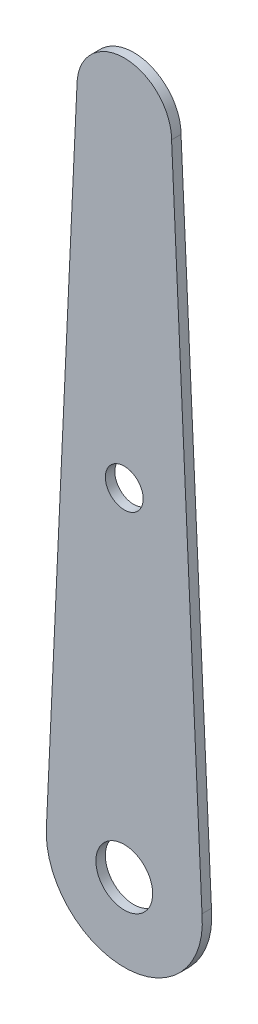
SolidWorks part; units mm, degrees
material "Galvanized Steel"
ref_plane "Front Plane" through (0, 0, 0) normal (0, 0, 1) x (1, 0, 0)
ref_plane "Top Plane" through (0, 0, 0) normal (0, 1, 0) x (1, 0, 0)
ref_plane "Right Plane" through (0, 0, 0) normal (1, 0, 0) x (0, 0, -1)
sketch "Sketch1" plane through (0, 0, 0) normal (0, 0, 1) x (1, 0, 0)
  line L0 (-16.429, -29.4883) -> (-10, 108.9829)
  line L1 (10, 108.9829) -> (16.429, -29.4883)
  arc A0 (-16.429, -29.4883) -> (16.429, -29.4883) centre (0, -31.0171) ccw
  arc A1 (10, 108.9829) -> (-10, 108.9829) centre (0, 108.9829) ccw
  circle A2 centre (0, 40.2429) radius 4
  dimension "D1" = 33
  dimension "D2" = 20
  dimension "D3" = 140
  dimension "D4" = 71.26
  dimension "D5" = 8
extrude "Boss-Extrude1" add sketch "Sketch1" along normal blind 2
sketch "Sketch2" plane through (0, 0, 2) normal (0, 0, 1) x (1, 0, 0)
  circle A0 centre (0, -31.0171) radius 6
  dimension "D1" = 12
extrude "Cut-Extrude1" cut sketch "Sketch2" against normal through all both and the other way through all
